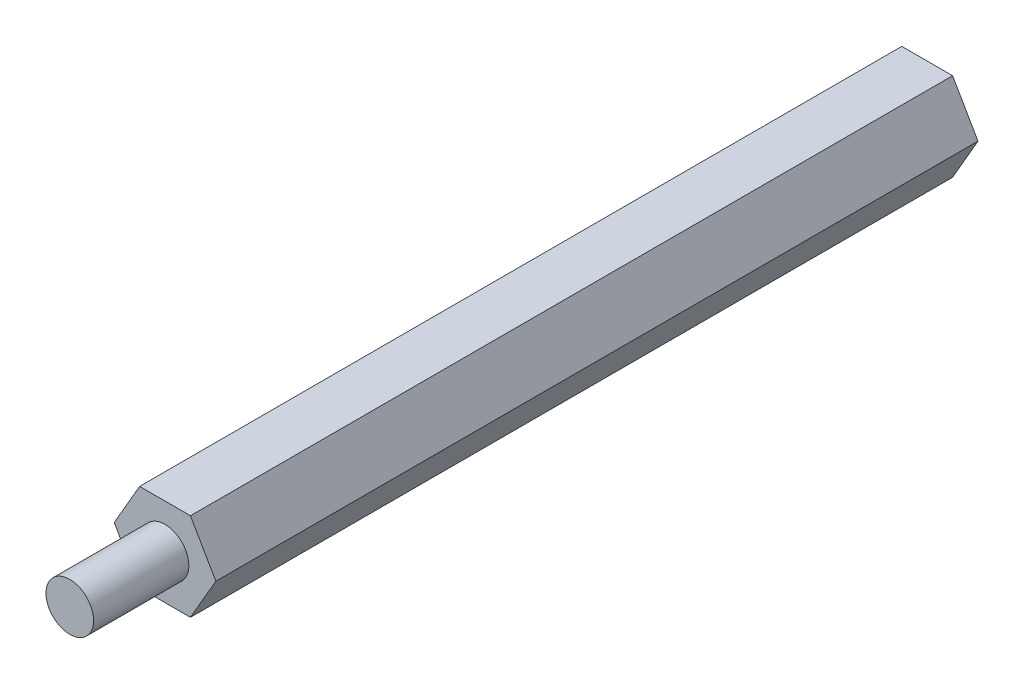
SolidWorks part; units mm, degrees
material "黄铜"
ref_plane "前视基准面" through (0, 0, 0) normal (0, 0, 1) x (1, 0, 0)
ref_plane "上视基准面" through (0, 0, 0) normal (0, 1, 0) x (1, 0, 0)
ref_plane "右视基准面" through (0, 0, 0) normal (1, 0, 0) x (0, 0, -1)
sketch "草图3" plane through (0, 0, 0) normal (0, 0, 1) x (1, 0, 0)
  line L1 (1.6, 2.7713) -> (-1.6, 2.7713)
  line L2 (-1.6, 2.7713) -> (-3.2, 0)
  line L3 (-3.2, 0) -> (-1.6, -2.7713)
  line L4 (-1.6, -2.7713) -> (1.6, -2.7713)
  line L5 (1.6, -2.7713) -> (3.2, 0)
  line L6 (3.2, 0) -> (1.6, 2.7713)
  circle A0 centre (0, 0) radius 2.7713 construction
  dimension "D1" = 3.2
extrude "凸台-拉伸1" add sketch "草图3" along normal blind 48
sketch "草图4" plane through (0, 0, 0) normal (0, 0, -1) x (-1, 0, 0)
  circle A0 centre (0, 0) radius 1.5
  dimension "D1" = 3
extrude "切除-拉伸1" cut sketch "草图4" against normal blind 6
sketch "草图5" plane through (0, 0, 48) normal (0, 0, 1) x (1, 0, 0)
  circle A0 centre (0, 0) radius 1.5
  dimension "D1" = 3
extrude "凸台-拉伸2" add sketch "草图5" along normal blind 6
